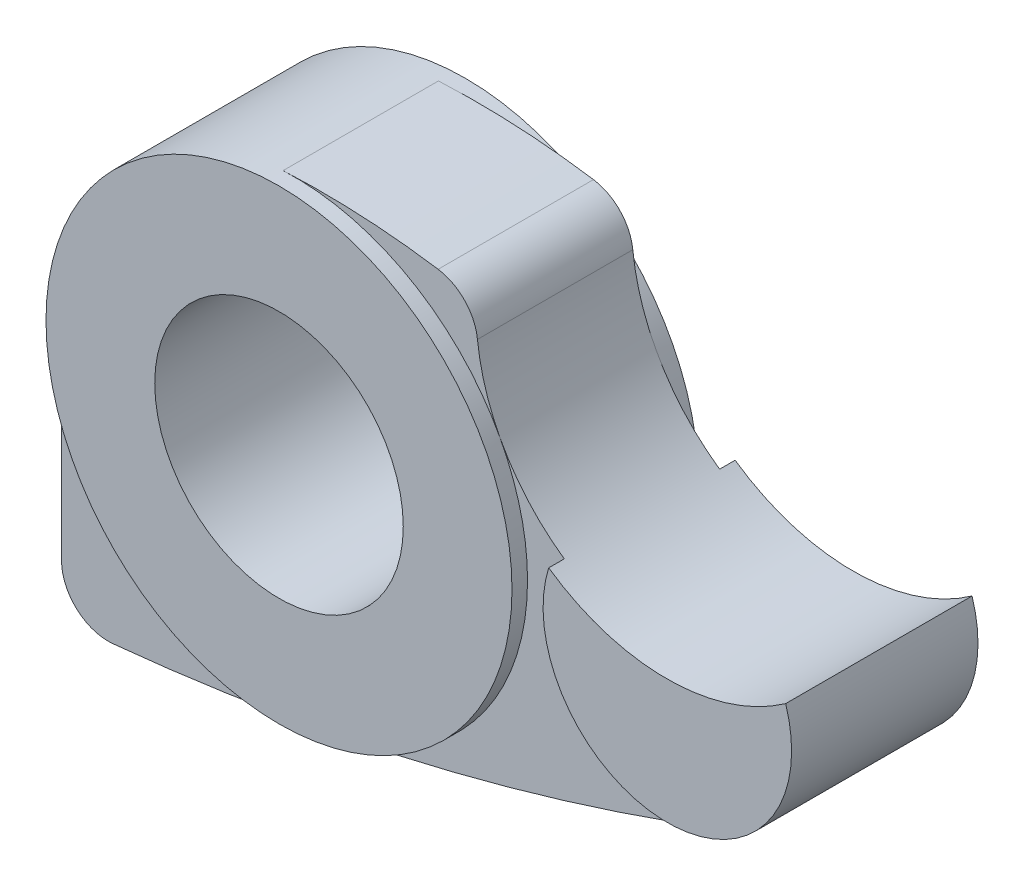
SolidWorks part; units mm, degrees
ref_plane "前视基准面" through (0, 0, 0) normal (0, 0, 1) x (1, 0, 0)
ref_plane "上视基准面" through (0, 0, 0) normal (0, 1, 0) x (1, 0, 0)
ref_plane "右视基准面" through (0, 0, 0) normal (1, 0, 0) x (0, 0, -1)
sketch "草图1" plane through (0, 0, 0) normal (0, 0, 1) x (1, 0, 0)
  line L0 (-15, 0) -> (-15, -13.8874)
  line L1 (55, 0) -> (-55, 0) construction
  arc A0 (-0.7371, 14.9819) -> (-15, 0) centre (0, 0) ccw
  arc A1 (-11.7086, -16.8732) -> (27.889, -7.4601) centre (-26.28, 132.4174) ccw
  arc A2 (17.3642, 2.3863) -> (32.6175, 2.444) centre (25, 0) ccw
  arc A3 (-15, -13.8874) -> (-11.7086, -16.8732) centre (-12, -13.8874) ccw
  arc A4 (9.2452, 14.4728) -> (-0.7371, 14.9819) centre (1.72, -34.9577) ccw
  arc A5 (11.7764, 11.8287) -> (32.6175, 2.444) centre (24.9499, 13.25) ccw
  arc A6 (29.4343, 6.6586) -> (11.723, 14.0315) centre (1.72, -34.9577) ccw construction
  arc A7 (29.4343, 6.6586) -> (17.3642, 2.3863) centre (25, 0) ccw construction
  arc A8 (32.6175, 2.444) -> (29.4343, 6.6586) centre (25, 0) ccw construction
  arc A9 (13.2478, 7.0354) -> (-0.7371, 14.9819) centre (0, 0) ccw construction
  arc A10 (-15, 0) -> (13.2478, 7.0354) centre (0, 0) ccw construction
  arc A11 (11.7764, 11.8287) -> (9.2452, 14.4728) centre (8.7937, 11.5069) ccw
  dimension "D1" = 30
  dimension "D2" = 16
  dimension "D4" = 3
  dimension "D5" = 50
  dimension "D6" = 26.5
  dimension "D7" = 150
  dimension "D8" = 3
  dimension "D3" = 25
extrude "凸台-拉伸1" add sketch "草图1" along normal mid plane 10 contours A5 A2 | A5 A11 A4 A0 L0 A3 A1 A2
sketch "草图2" plane through (0, 0, 0) normal (0, 0, 1) x (1, 0, 0)
  arc A0 (-15, 0) -> (13.2478, 7.0354) centre (0, 0) ccw construction
  arc A1 (-15, 0) -> (13.2478, 7.0354) centre (0, 0) ccw
  arc A2 (-0.7371, 14.9819) -> (-15, 0) centre (0, 0) ccw construction
  arc A3 (13.2478, 7.0354) -> (-0.7371, 14.9819) centre (0, 0) ccw construction
  arc A4 (-0.7371, 14.9819) -> (-15, 0) centre (0, 0) ccw
  arc A5 (13.2478, 7.0354) -> (-0.7371, 14.9819) centre (0, 0) ccw
extrude "凸台-拉伸2" add sketch "草图2" along normal mid plane 12
sketch "草图3" plane through (0, 0, 0) normal (0, 0, 1) x (1, 0, 0)
  arc A0 (17.3642, 2.3863) -> (32.6175, 2.444) centre (25, 0) ccw construction
  arc A1 (11.7764, 11.8287) -> (32.6175, 2.444) centre (24.9499, 13.25) ccw construction
  arc A2 (17.3642, 2.3863) -> (32.6175, 2.444) centre (25, 0) ccw
  arc A3 (17.3642, 2.3863) -> (32.6175, 2.444) centre (24.9499, 13.25) ccw
  arc A4 (11.7764, 11.8287) -> (17.3642, 2.3863) centre (24.9499, 13.25) ccw construction
extrude "凸台-拉伸3" add sketch "草图3" along normal mid plane 12
sketch "草图4" plane through (0, 0, 6) normal (0, 0, 1) x (1, 0, 0)
  circle A0 centre (0, 0) radius 8
  dimension "D1" = 16
extrude "切除-拉伸1" cut sketch "草图4" against normal through all
